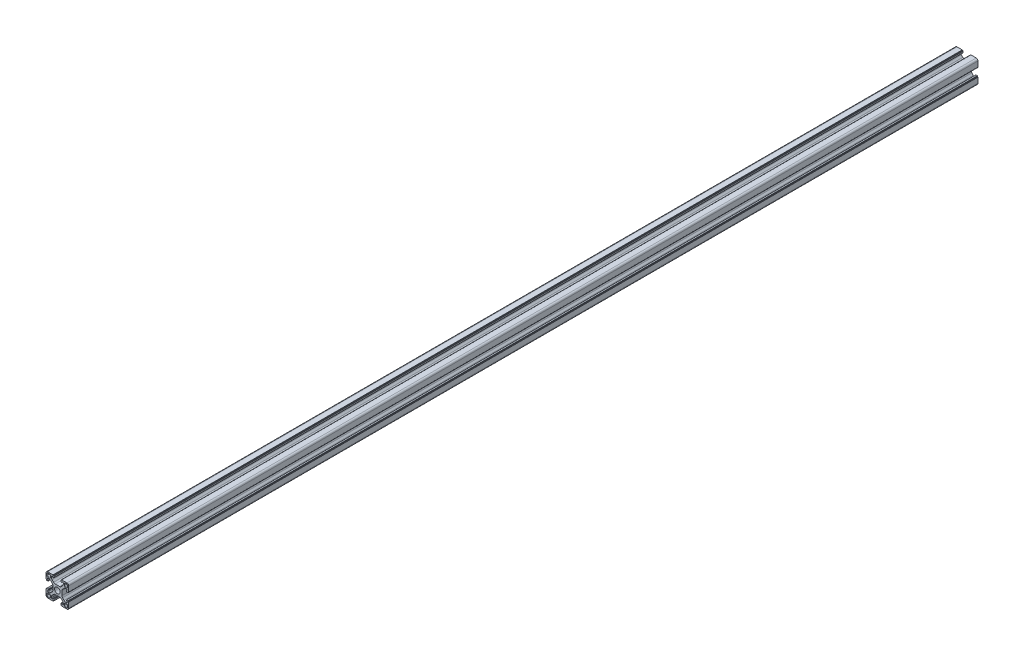
SolidWorks part; units mm, degrees
ref_plane "Спереди" through (0, 0, 0) normal (0, 0, 1) x (1, 0, 0)
ref_plane "Сверху" through (0, 0, 0) normal (0, 1, 0) x (1, 0, 0)
ref_plane "Справа" through (0, 0, 0) normal (1, 0, 0) x (0, 0, -1)
sketch "Эскиз2" plane through (0, 0, 0) normal (0, 0, 1) x (1, 0, 0)
  line L0 (9.2299, 9.7837) -> (6.2299, 6.7837) construction
  line L1 (0.1299, 4.6837) -> (2.0286, 4.6837)
  line L2 (0.1299, 0.6837) -> (10.1299, 10.6837) construction
  line L3 (7.7299, 8.2837) -> (6.2299, 9.7837) construction
  line L4 (3.4428, 5.2695) -> (4.7441, 6.5707)
  line L5 (7.0299, 6.7837) -> (8.4299, 6.7837)
  line L6 (6.2299, 7.5837) -> (6.2299, 8.9837)
  line L7 (8.4299, 9.7837) -> (7.0299, 9.7837)
  line L8 (5.3299, 8.8837) -> (5.3299, 7.9849)
  line L9 (3.8931, 8.757) -> (4.3734, 9.2373)
  line L10 (3.3299, 10.2328) -> (3.8299, 10.2328)
  line L11 (3.7163, 8.6837) -> (3.4299, 8.6837)
  line L12 (4.727, 9.3837) -> (4.8299, 9.3837)
  line L13 (3.8299, 10.5337) -> (3.8299, 10.2328)
  line L14 (3.1799, 10.0828) -> (3.1799, 8.9337)
  line L15 (8.6299, 10.6837) -> (3.9799, 10.6837)
  line L16 (9.2299, 8.9837) -> (9.2299, 7.5837)
  line L17 (10.1299, 9.1837) -> (10.1299, 4.5337)
  line L18 (9.5289, 3.7337) -> (8.3799, 3.7337)
  line L19 (9.9799, 4.3837) -> (9.6789, 4.3837)
  line L20 (8.8299, 5.2808) -> (8.8299, 5.3837)
  line L21 (8.1299, 4.2702) -> (8.1299, 3.9837)
  line L22 (9.6789, 3.8837) -> (9.6789, 4.3837)
  line L23 (8.2031, 4.447) -> (8.6834, 4.9273)
  line L24 (8.3299, 5.8837) -> (7.4311, 5.8837)
  line L25 (4.7156, 3.9967) -> (6.0169, 5.2979)
  line L26 (4.1299, 0.6837) -> (4.1299, 2.5825)
  line L27 (4.1299, 0.6837) -> (4.1299, -1.2151)
  line L28 (4.7156, -2.6293) -> (6.0169, -3.9305)
  line L29 (6.2299, -6.2163) -> (6.2299, -7.6163)
  line L30 (7.0299, -5.4163) -> (8.4299, -5.4163)
  line L31 (9.2299, -7.6163) -> (9.2299, -6.2163)
  line L32 (8.3299, -4.5163) -> (7.4311, -4.5163)
  line L33 (8.2031, -3.0795) -> (8.6834, -3.5598)
  line L34 (9.6789, -2.5163) -> (9.6789, -3.0163)
  line L35 (8.1299, -2.9027) -> (8.1299, -2.6163)
  line L36 (8.8299, -3.9134) -> (8.8299, -4.0163)
  line L37 (9.9799, -3.0163) -> (9.6789, -3.0163)
  line L38 (9.5289, -2.3663) -> (8.3799, -2.3663)
  line L39 (10.1299, -7.8163) -> (10.1299, -3.1663)
  line L40 (8.4299, -8.4163) -> (7.0299, -8.4163)
  line L41 (8.6299, -9.3163) -> (3.9799, -9.3163)
  line L42 (3.1799, -8.7153) -> (3.1799, -7.5663)
  line L43 (3.8299, -9.1663) -> (3.8299, -8.8653)
  line L44 (4.727, -8.0163) -> (4.8299, -8.0163)
  line L45 (3.7163, -7.3163) -> (3.4299, -7.3163)
  line L46 (3.3299, -8.8653) -> (3.8299, -8.8653)
  line L47 (3.8931, -7.3895) -> (4.3734, -7.8698)
  line L48 (5.3299, -7.5163) -> (5.3299, -6.6175)
  line L49 (3.4428, -3.9021) -> (4.7441, -5.2033)
  line L50 (0.1299, -3.3163) -> (2.0286, -3.3163)
  line L51 (9.2299, -8.4163) -> (6.2299, -5.4163) construction
  line L52 (0.1299, 0.6837) -> (10.1299, -9.3163) construction
  line L53 (7.7299, -6.9163) -> (9.2299, -5.4163) construction
  line L54 (0.1299, -3.3163) -> (-1.7689, -3.3163)
  line L55 (-3.1831, -3.9021) -> (-4.4844, -5.2033)
  line L56 (-6.7701, -5.4163) -> (-8.1701, -5.4163)
  line L57 (-5.9701, -6.2163) -> (-5.9701, -7.6163)
  line L58 (-8.1701, -8.4163) -> (-6.7701, -8.4163)
  line L59 (-5.0701, -7.5163) -> (-5.0701, -6.6175)
  line L60 (-3.6334, -7.3895) -> (-4.1137, -7.8698)
  line L61 (-3.0701, -8.8653) -> (-3.5701, -8.8653)
  line L62 (-3.4566, -7.3163) -> (-3.1701, -7.3163)
  line L63 (-4.4673, -8.0163) -> (-4.5701, -8.0163)
  line L64 (-3.5701, -9.1663) -> (-3.5701, -8.8653)
  line L65 (-2.9201, -8.7153) -> (-2.9201, -7.5663)
  line L66 (-8.3701, -9.3163) -> (-3.7201, -9.3163)
  line L67 (-8.9701, -7.6163) -> (-8.9701, -6.2163)
  line L68 (-9.8701, -7.8163) -> (-9.8701, -3.1663)
  line L69 (-9.2692, -2.3663) -> (-8.1201, -2.3663)
  line L70 (-9.7201, -3.0163) -> (-9.4192, -3.0163)
  line L71 (-8.5701, -3.9134) -> (-8.5701, -4.0163)
  line L72 (-7.8701, -2.9027) -> (-7.8701, -2.6163)
  line L73 (-9.4192, -2.5163) -> (-9.4192, -3.0163)
  line L74 (-7.9434, -3.0795) -> (-8.4237, -3.5598)
  line L75 (-8.0701, -4.5163) -> (-7.1714, -4.5163)
  line L76 (-4.4559, -2.6293) -> (-5.7572, -3.9305)
  line L77 (-3.8701, 0.6837) -> (-3.8701, -1.2151)
  line L78 (-8.9701, -8.4163) -> (-5.9701, -5.4163) construction
  line L79 (0.1299, 0.6837) -> (-9.8701, -9.3163) construction
  line L80 (-7.4701, -6.9163) -> (-5.9701, -8.4163) construction
  line L81 (-3.8701, 0.6837) -> (-3.8701, 2.5825)
  line L82 (-4.4559, 3.9967) -> (-5.7572, 5.2979)
  line L83 (-5.9701, 7.5837) -> (-5.9701, 8.9837)
  line L84 (-6.7701, 6.7837) -> (-8.1701, 6.7837)
  line L85 (-8.9701, 8.9837) -> (-8.9701, 7.5837)
  line L86 (-8.0701, 5.8837) -> (-7.1714, 5.8837)
  line L87 (-7.9434, 4.447) -> (-8.4237, 4.9273)
  line L88 (-9.4192, 3.8837) -> (-9.4192, 4.3837)
  line L89 (-7.8701, 4.2702) -> (-7.8701, 3.9837)
  line L90 (-8.5701, 5.2808) -> (-8.5701, 5.3837)
  line L91 (-9.7201, 4.3837) -> (-9.4192, 4.3837)
  line L92 (-9.2692, 3.7337) -> (-8.1201, 3.7337)
  line L93 (-9.8701, 9.1837) -> (-9.8701, 4.5337)
  line L94 (-8.1701, 9.7837) -> (-6.7701, 9.7837)
  line L95 (-8.3701, 10.6837) -> (-3.7201, 10.6837)
  line L96 (-2.9201, 10.0828) -> (-2.9201, 8.9337)
  line L97 (-3.5701, 10.5337) -> (-3.5701, 10.2328)
  line L98 (-4.4673, 9.3837) -> (-4.5701, 9.3837)
  line L99 (-3.4566, 8.6837) -> (-3.1701, 8.6837)
  line L100 (-3.0701, 10.2328) -> (-3.5701, 10.2328)
  line L101 (-3.6334, 8.757) -> (-4.1137, 9.2373)
  line L102 (-5.0701, 8.8837) -> (-5.0701, 7.9849)
  line L103 (-3.1831, 5.2695) -> (-4.4844, 6.5707)
  line L104 (0.1299, 4.6837) -> (-1.7689, 4.6837)
  line L105 (-11.6342, 0.6837) -> (11.6342, 0.6837) construction
  line L106 (-8.9701, 9.7837) -> (-5.9701, 6.7837) construction
  line L107 (0.1299, -11.4027) -> (0.1299, 11.4027) construction
  line L108 (0.1299, 0.6837) -> (-9.8701, 10.6837) construction
  line L109 (-7.4701, 8.2837) -> (-8.9701, 6.7837) construction
  arc A0 (9.2299, 8.9837) -> (8.4299, 9.7837) centre (8.4299, 8.9837) ccw
  arc A1 (7.0299, 9.7837) -> (6.2299, 8.9837) centre (7.0299, 8.9837) ccw
  arc A2 (7.0299, 6.7837) -> (6.2299, 7.5837) centre (7.0299, 7.5837) cw
  arc A3 (8.6299, 10.6837) -> (10.1299, 9.1837) centre (8.6299, 9.1837) cw
  arc A4 (3.3299, 10.2328) -> (3.1799, 10.0828) centre (3.3299, 10.0828) ccw
  arc A5 (3.9799, 10.6837) -> (3.8299, 10.5337) centre (3.9799, 10.5337) ccw
  arc A6 (3.7163, 8.6837) -> (3.8931, 8.757) centre (3.7163, 8.9337) ccw
  arc A7 (3.4299, 8.6837) -> (3.1799, 8.9337) centre (3.4299, 8.9337) cw
  arc A8 (4.3734, 9.2373) -> (4.727, 9.3837) centre (4.727, 8.8837) cw
  arc A9 (4.8299, 9.3837) -> (5.3299, 8.8837) centre (4.8299, 8.8837) cw
  arc A10 (2.6299, 0.6837) -> (0.1299, 3.1837) centre (0.1299, 0.6837) ccw
  arc A11 (2.0286, 4.6837) -> (3.4428, 5.2695) centre (2.0286, 6.6837) ccw
  arc A12 (5.3299, 7.9849) -> (4.7441, 6.5707) centre (3.3299, 7.9849) cw
  arc A13 (9.2299, 7.5837) -> (8.4299, 6.7837) centre (8.4299, 7.5837) cw
  arc A14 (8.8299, 5.3837) -> (8.3299, 5.8837) centre (8.3299, 5.3837) ccw
  arc A15 (8.6834, 4.9273) -> (8.8299, 5.2808) centre (8.3299, 5.2808) ccw
  arc A16 (8.1299, 3.9837) -> (8.3799, 3.7337) centre (8.3799, 3.9837) ccw
  arc A17 (8.1299, 4.2702) -> (8.2031, 4.447) centre (8.3799, 4.2702) cw
  arc A18 (10.1299, 4.5337) -> (9.9799, 4.3837) centre (9.9799, 4.5337) cw
  arc A19 (9.6789, 3.8837) -> (9.5289, 3.7337) centre (9.5289, 3.8837) cw
  arc A20 (7.4311, 5.8837) -> (6.0169, 5.2979) centre (7.4311, 3.8837) ccw
  arc A21 (4.1299, 2.5825) -> (4.7156, 3.9967) centre (6.1299, 2.5825) cw
  arc A22 (8.4299, -8.4163) -> (9.2299, -7.6163) centre (8.4299, -7.6163) ccw
  arc A23 (9.2299, -6.2163) -> (8.4299, -5.4163) centre (8.4299, -6.2163) ccw
  arc A24 (6.2299, -6.2163) -> (7.0299, -5.4163) centre (7.0299, -6.2163) cw
  arc A25 (10.1299, -7.8163) -> (8.6299, -9.3163) centre (8.6299, -7.8163) cw
  arc A26 (9.6789, -2.5163) -> (9.5289, -2.3663) centre (9.5289, -2.5163) ccw
  arc A27 (10.1299, -3.1663) -> (9.9799, -3.0163) centre (9.9799, -3.1663) ccw
  arc A28 (8.1299, -2.9027) -> (8.2031, -3.0795) centre (8.3799, -2.9027) ccw
  arc A29 (8.1299, -2.6163) -> (8.3799, -2.3663) centre (8.3799, -2.6163) cw
  arc A30 (8.6834, -3.5598) -> (8.8299, -3.9134) centre (8.3299, -3.9134) cw
  arc A31 (8.8299, -4.0163) -> (8.3299, -4.5163) centre (8.3299, -4.0163) cw
  arc A32 (0.1299, -1.8163) -> (2.6299, 0.6837) centre (0.1299, 0.6837) ccw
  arc A33 (4.1299, -1.2151) -> (4.7156, -2.6293) centre (6.1299, -1.2151) ccw
  arc A34 (7.4311, -4.5163) -> (6.0169, -3.9305) centre (7.4311, -2.5163) cw
  arc A35 (7.0299, -8.4163) -> (6.2299, -7.6163) centre (7.0299, -7.6163) cw
  arc A36 (4.8299, -8.0163) -> (5.3299, -7.5163) centre (4.8299, -7.5163) ccw
  arc A37 (4.3734, -7.8698) -> (4.727, -8.0163) centre (4.727, -7.5163) ccw
  arc A38 (3.4299, -7.3163) -> (3.1799, -7.5663) centre (3.4299, -7.5663) ccw
  arc A39 (3.7163, -7.3163) -> (3.8931, -7.3895) centre (3.7163, -7.5663) cw
  arc A40 (3.9799, -9.3163) -> (3.8299, -9.1663) centre (3.9799, -9.1663) cw
  arc A41 (3.3299, -8.8653) -> (3.1799, -8.7153) centre (3.3299, -8.7153) cw
  arc A42 (5.3299, -6.6175) -> (4.7441, -5.2033) centre (3.3299, -6.6175) ccw
  arc A43 (2.0286, -3.3163) -> (3.4428, -3.9021) centre (2.0286, -5.3163) cw
  arc A44 (-8.9701, -7.6163) -> (-8.1701, -8.4163) centre (-8.1701, -7.6163) ccw
  arc A45 (-6.7701, -8.4163) -> (-5.9701, -7.6163) centre (-6.7701, -7.6163) ccw
  arc A46 (-6.7701, -5.4163) -> (-5.9701, -6.2163) centre (-6.7701, -6.2163) cw
  arc A47 (-8.3701, -9.3163) -> (-9.8701, -7.8163) centre (-8.3701, -7.8163) cw
  arc A48 (-3.0701, -8.8653) -> (-2.9201, -8.7153) centre (-3.0701, -8.7153) ccw
  arc A49 (-3.7201, -9.3163) -> (-3.5701, -9.1663) centre (-3.7201, -9.1663) ccw
  arc A50 (-3.4566, -7.3163) -> (-3.6334, -7.3895) centre (-3.4566, -7.5663) ccw
  arc A51 (-3.1701, -7.3163) -> (-2.9201, -7.5663) centre (-3.1701, -7.5663) cw
  arc A52 (-4.1137, -7.8698) -> (-4.4673, -8.0163) centre (-4.4673, -7.5163) cw
  arc A53 (-4.5701, -8.0163) -> (-5.0701, -7.5163) centre (-4.5701, -7.5163) cw
  arc A54 (-2.3701, 0.6837) -> (0.1299, -1.8163) centre (0.1299, 0.6837) ccw
  arc A55 (-1.7689, -3.3163) -> (-3.1831, -3.9021) centre (-1.7689, -5.3163) ccw
  arc A56 (-5.0701, -6.6175) -> (-4.4844, -5.2033) centre (-3.0701, -6.6175) cw
  arc A57 (-8.9701, -6.2163) -> (-8.1701, -5.4163) centre (-8.1701, -6.2163) cw
  arc A58 (-8.5701, -4.0163) -> (-8.0701, -4.5163) centre (-8.0701, -4.0163) ccw
  arc A59 (-8.4237, -3.5598) -> (-8.5701, -3.9134) centre (-8.0701, -3.9134) ccw
  arc A60 (-7.8701, -2.6163) -> (-8.1201, -2.3663) centre (-8.1201, -2.6163) ccw
  arc A61 (-7.8701, -2.9027) -> (-7.9434, -3.0795) centre (-8.1201, -2.9027) cw
  arc A62 (-9.8701, -3.1663) -> (-9.7201, -3.0163) centre (-9.7201, -3.1663) cw
  arc A63 (-9.4192, -2.5163) -> (-9.2692, -2.3663) centre (-9.2692, -2.5163) cw
  arc A64 (-7.1714, -4.5163) -> (-5.7572, -3.9305) centre (-7.1714, -2.5163) ccw
  arc A65 (-3.8701, -1.2151) -> (-4.4559, -2.6293) centre (-5.8701, -1.2151) cw
  arc A66 (-8.1701, 9.7837) -> (-8.9701, 8.9837) centre (-8.1701, 8.9837) ccw
  arc A67 (-8.9701, 7.5837) -> (-8.1701, 6.7837) centre (-8.1701, 7.5837) ccw
  arc A68 (-5.9701, 7.5837) -> (-6.7701, 6.7837) centre (-6.7701, 7.5837) cw
  arc A69 (-9.8701, 9.1837) -> (-8.3701, 10.6837) centre (-8.3701, 9.1837) cw
  arc A70 (-9.4192, 3.8837) -> (-9.2692, 3.7337) centre (-9.2692, 3.8837) ccw
  arc A71 (-9.8701, 4.5337) -> (-9.7201, 4.3837) centre (-9.7201, 4.5337) ccw
  arc A72 (-7.8701, 4.2702) -> (-7.9434, 4.447) centre (-8.1201, 4.2702) ccw
  arc A73 (-7.8701, 3.9837) -> (-8.1201, 3.7337) centre (-8.1201, 3.9837) cw
  arc A74 (-8.4237, 4.9273) -> (-8.5701, 5.2808) centre (-8.0701, 5.2808) cw
  arc A75 (-8.5701, 5.3837) -> (-8.0701, 5.8837) centre (-8.0701, 5.3837) cw
  arc A76 (0.1299, 3.1837) -> (-2.3701, 0.6837) centre (0.1299, 0.6837) ccw
  arc A77 (-3.8701, 2.5825) -> (-4.4559, 3.9967) centre (-5.8701, 2.5825) ccw
  arc A78 (-7.1714, 5.8837) -> (-5.7572, 5.2979) centre (-7.1714, 3.8837) cw
  arc A79 (-6.7701, 9.7837) -> (-5.9701, 8.9837) centre (-6.7701, 8.9837) cw
  arc A80 (-4.5701, 9.3837) -> (-5.0701, 8.8837) centre (-4.5701, 8.8837) ccw
  arc A81 (-4.1137, 9.2373) -> (-4.4673, 9.3837) centre (-4.4673, 8.8837) ccw
  arc A82 (-3.1701, 8.6837) -> (-2.9201, 8.9337) centre (-3.1701, 8.9337) ccw
  arc A83 (-3.4566, 8.6837) -> (-3.6334, 8.757) centre (-3.4566, 8.9337) cw
  arc A84 (-3.7201, 10.6837) -> (-3.5701, 10.5337) centre (-3.7201, 10.5337) cw
  arc A85 (-3.0701, 10.2328) -> (-2.9201, 10.0828) centre (-3.0701, 10.0828) cw
  arc A86 (-5.0701, 7.9849) -> (-4.4844, 6.5707) centre (-3.0701, 7.9849) ccw
  arc A87 (-1.7689, 4.6837) -> (-3.1831, 5.2695) centre (-1.7689, 6.6837) cw
  point P0 (0.1299, 0.6837)
  point P9 (0.1299, 0.6837)
  point P40 (8.8299, 4.3837)
  point P93 (3.8299, -8.0163)
  point P144 (3.8299, 9.3837)
  point P152 (8.8299, -3.0163)
  point P153 (0.1299, -3.2405)
  point P154 (0.1299, 0.6837)
  point P189 (-8.5701, -3.0163)
  point P228 (-3.5701, -8.0163)
  point P229 (-3.7944, 0.6837)
  point P230 (0.1299, 0.6837)
  point P268 (-3.5701, 9.3837)
  point P273 (4.0541, 0.6837)
  point P306 (-8.5701, 4.3837)
  point P307 (0.1299, 4.608)
  point P309 (0.1299, 0.6837)
  dimension "D3" = 5
  dimension "D6" = 2
  dimension "D1" = 2
  dimension "D2" = 6
  dimension "D4" = 4
  dimension "D5" = 0.9
extrude "Бобышка-Вытянуть1" add sketch "Эскиз2" along normal blind 800
